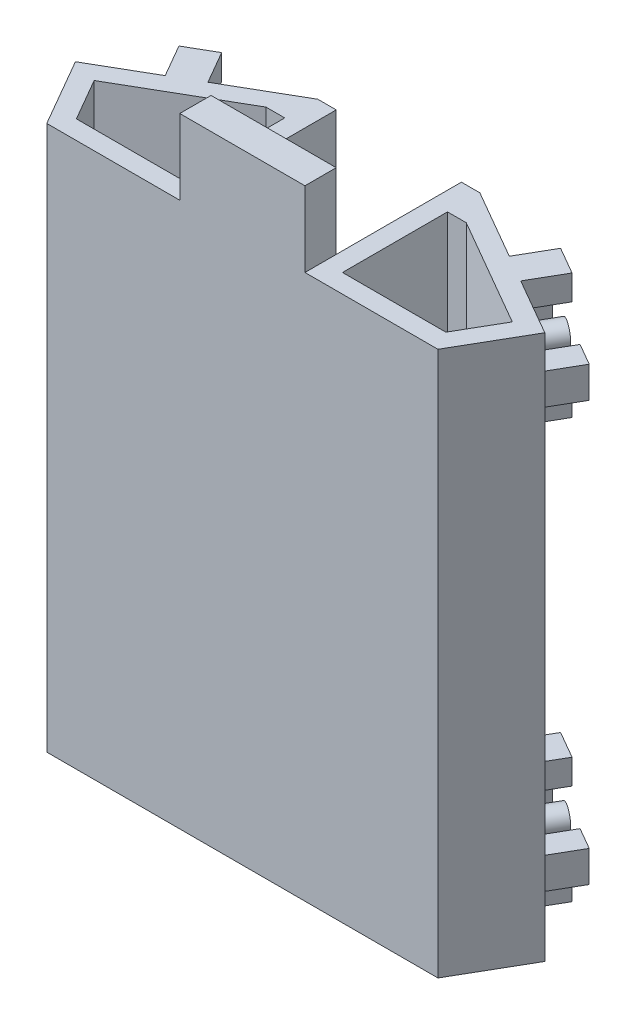
SolidWorks part; units mm, degrees
ref_plane "Plan de face" through (0, 0, 0) normal (0, 0, 1) x (1, 0, 0)
ref_plane "Plan de dessus" through (0, 0, 0) normal (0, 1, 0) x (1, 0, 0)
ref_plane "Plan de droite" through (0, 0, 0) normal (1, 0, 0) x (0, 0, -1)
sketch "Esquisse1" plane through (0, 0, 0) normal (0, 1, 0) x (1, 0, 0)
  line L0 (-31.25, 0) -> (31.25, 0)
  line L1 (31.25, 0) -> (37.5, 10.8253)
  line L2 (37.5, 10.8253) -> (12.9487, 25)
  line L3 (12.9487, 25) -> (10, 25)
  line L4 (10, 25) -> (10, 5)
  line L5 (10, 5) -> (-10, 5)
  line L6 (-10, 5) -> (-10, 25)
  line L7 (-10, 25) -> (-12.9487, 25)
  line L8 (-12.9487, 25) -> (-37.5, 10.8253)
  line L9 (-37.5, 10.8253) -> (-31.25, 0)
  line L10 (0, 5) -> (0, 0) construction
  dimension "D1" = 120
  dimension "D2" = 5
  dimension "D3" = 20
  dimension "D4" = 62.5
  dimension "D5" = 12.5
extrude "Boss.-Extru.1" add sketch "Esquisse1" along normal blind 87
sketch "Esquisse2" plane through (0, 87, 0) normal (0, 1, 0) x (1, 0, 0)
  line L0 (-36, 8.2272) -> (-16, 19.7742)
  line L1 (-16, 19.7742) -> (-13, 19.7742)
  line L3 (-37.5, 10.8253) -> (-12.9487, 25) construction
  line L4 (-31.25, 0) -> (-37.5, 10.8253) construction
  line L6 (-13, 19.7742) -> (-13, 0)
  line L7 (31.25, 0) -> (-31.25, 0) construction
  line L8 (-13, 0) -> (-31.25, 0)
  line L9 (-31.25, 0) -> (-36, 8.2272)
  line L10 (-10, 25) -> (-10, 5) construction
  dimension "D1" = 3
  dimension "D2" = 3
  dimension "D3" = 3
extrude "Enlèv. mat.-Extru.1" cut sketch "Esquisse2" against normal up to next
mirror "Symétrie1" about plane through (0, 0, 0) normal (1, 0, 0) of "Enlèv. mat.-Extru.1"
sketch "Esquisse3" plane through (-14.0625, 0, -24.357) normal (0.5, 0, 0.866) x (0.866, 0, -0.5)
  line L0 (-27.0633, 87) -> (-27.0633, 0) construction
  line L4 (-3.9693, 87) -> (-27.0633, 87) construction
  line L5 (-14.0633, 83) -> (-14.0633, 71) construction
  line L6 (-11.5633, 87) -> (-16.5633, 87)
  line L7 (-11.5633, 87) -> (-11.5633, 83)
  line L8 (-11.5633, 83) -> (-16.5633, 83)
  line L9 (-16.5633, 87) -> (-16.5633, 83)
  line L10 (-20.0633, 79.5) -> (-24.0633, 79.5)
  line L11 (-20.0633, 79.5) -> (-20.0633, 74.5)
  line L12 (-20.0633, 74.5) -> (-24.0633, 74.5)
  line L13 (-24.0633, 79.5) -> (-24.0633, 74.5)
  line L14 (-4.0633, 79.5) -> (-8.0633, 79.5)
  line L15 (-4.0633, 79.5) -> (-4.0633, 74.5)
  line L16 (-4.0633, 74.5) -> (-8.0633, 74.5)
  line L17 (-8.0633, 79.5) -> (-8.0633, 74.5)
  line L18 (-11.5633, 71) -> (-16.5633, 71)
  line L19 (-11.5633, 71) -> (-11.5633, 67)
  line L20 (-11.5633, 67) -> (-16.5633, 67)
  line L21 (-16.5633, 71) -> (-16.5633, 67)
  line L23 (-8.0633, 77) -> (-20.0633, 77) construction
  circle A1 centre (-14.0633, 77) radius 1.9
  dimension "D1" = 5
  dimension "D2" = 4
  dimension "D3" = 10
  dimension "D4" = 3.8
  dimension "D5" = 20
  dimension "D6" = 13
sketch "Esquisse4" plane through (0, 0, 0) normal (0, 1, 0) x (1, 0, 0)
  line L0 (-37.5, 10.8253) -> (-31.25, 0)
  line L1 (-31.25, 0) -> (31.25, 0)
  line L2 (31.25, 0) -> (37.5, 10.8253)
  line L3 (12.9487, 25) -> (37.5, 10.8253) construction
  line L4 (37.5, 10.8253) -> (36, 8.2272) construction
  line L5 (-36, 8.2272) -> (-37.5, 10.8253) construction
  line L6 (-37.5, 10.8253) -> (-34.9019, 12.3253)
  line L7 (-37.5, 10.8253) -> (-12.9487, 25) construction
  line L8 (-34.9019, 12.3253) -> (-29.5179, 3)
  line L9 (-29.5179, 3) -> (29.5179, 3)
  line L10 (29.5179, 3) -> (34.9019, 12.3253)
  line L11 (34.9019, 12.3253) -> (37.5, 10.8253)
  line L12 (0, 0) -> (0, 3) construction
  dimension "D1" = 3
extrude "Boss.-Extru.2" add sketch "Esquisse4" along normal up to surface (87 mm away) up to face at (0, 87, -14.2001)
extrude "Boss.-Extru.3" add sketch "Esquisse3" against normal blind 6
ref_plane "Plan1" through (0, 43.5, 0) normal (0, 1, 0) x (1, 0, 0)
mirror "Symétrie2" about plane through (0, 43.5, 0) normal (0, 1, 0) of "Boss.-Extru.3"
mirror "Symétrie3" about plane through (0, 0, 0) normal (1, 0, 0) of "Symétrie2", "Boss.-Extru.3"
sketch "Esquisse5" plane through (0, 87, 0) normal (0, 1, 0) x (1, 0, 0)
  line L0 (31.25, 0) -> (-31.25, 0) construction
  line L1 (-10, 5) -> (10, 5)
  line L2 (-10, 5) -> (-10, 0)
  line L3 (-10, 0) -> (10, 0)
  line L4 (10, 5) -> (10, 0)
  line L5 (10, 5) -> (10, 25) construction
extrude "Boss.-Extru.4" add sketch "Esquisse5" along normal blind 12
